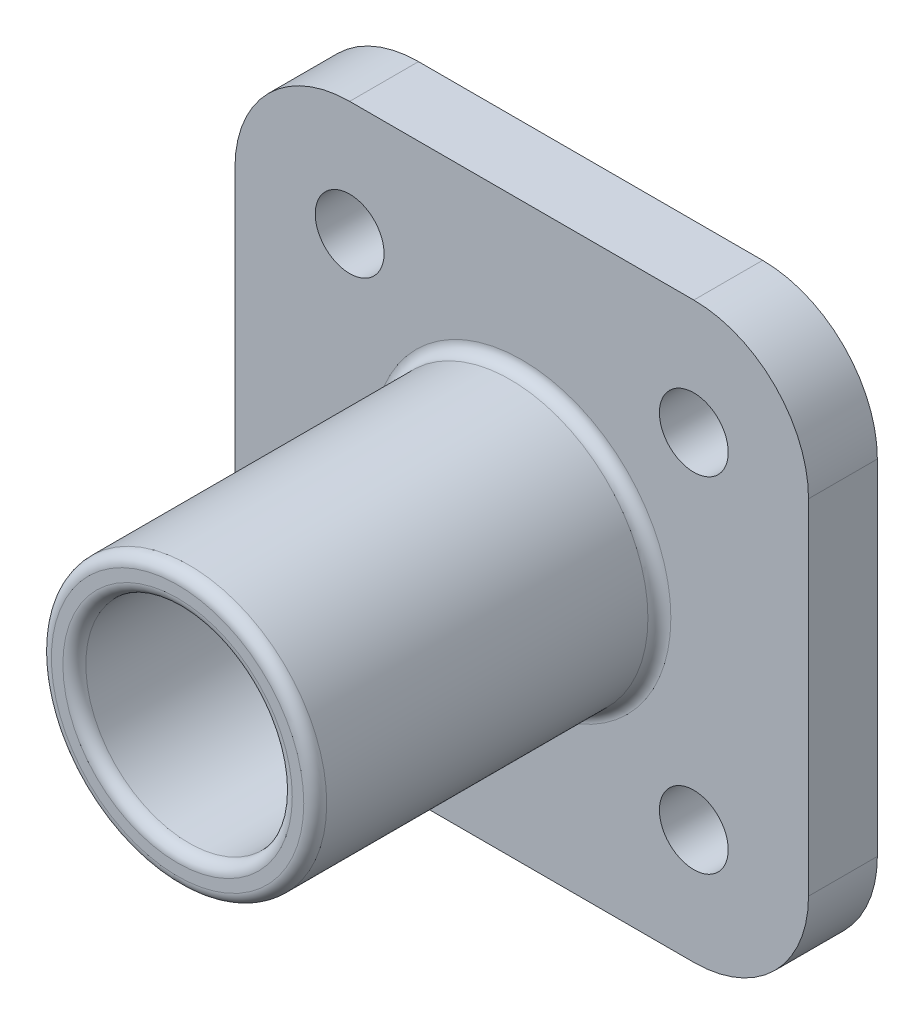
SolidWorks part; units mm, degrees
ref_plane "Plan de face" through (0, 0, 0) normal (0, 0, 1) x (1, 0, 0)
ref_plane "Plan de dessus" through (0, 0, 0) normal (0, 1, 0) x (1, 0, 0)
ref_plane "Plan de droite" through (0, 0, 0) normal (1, 0, 0) x (0, 0, -1)
sketch "Esquisse1" plane through (0, 0, 0) normal (0, 0, 1) x (1, 0, 0)
  line L0 (-7.5, 7.5) -> (7.5, 7.5) construction
  line L1 (7.5, -12.5) -> (-7.5, -12.5)
  line L2 (12.5, -7.5) -> (12.5, 7.5)
  line L3 (7.5, 12.5) -> (-7.5, 12.5)
  line L4 (-12.5, -7.5) -> (-12.5, 7.5)
  line L5 (12.5, -12.5) -> (-12.5, 12.5) construction
  line L6 (12.5, 12.5) -> (-12.5, -12.5) construction
  line L7 (-7.5, 7.5) -> (-7.5, -7.5) construction
  arc A0 (7.5, -12.5) -> (12.5, -7.5) centre (7.5, -7.5) ccw
  arc A1 (-7.5, -12.5) -> (-12.5, -7.5) centre (-7.5, -7.5) cw
  arc A2 (12.5, 7.5) -> (7.5, 12.5) centre (7.5, 7.5) ccw
  arc A3 (-7.5, 12.5) -> (-12.5, 7.5) centre (-7.5, 7.5) ccw
  circle A4 centre (-7.5, 7.5) radius 1.5
  circle A5 centre (7.5, 7.5) radius 1.5
  circle A6 centre (7.5, -7.5) radius 1.5
  circle A7 centre (-7.5, -7.5) radius 1.5
  point P0 (0, 0)
  dimension "D2" = 5
  dimension "D3" = 3
  dimension "D1" = 25
  dimension "D4" = 2
  dimension "D5" = 2
extrude "Boss.-Extru.1" add sketch "Esquisse1" along normal blind 3
sketch "Esquisse2" plane through (0, 0, 3) normal (0, 0, 1) x (1, 0, 0)
  circle A0 centre (0, 0) radius 6
  circle A1 centre (0, 0) radius 4.5
  dimension "D1" = 9
  dimension "D2" = 12
extrude "Boss.-Extru.2" add sketch "Esquisse2" along normal blind 15 contours A0 | A1
fillet "Congé1" radius 0.5 3 edges at (6, 0, 3) (6, 0, 18) (4.5, 0, 18)
